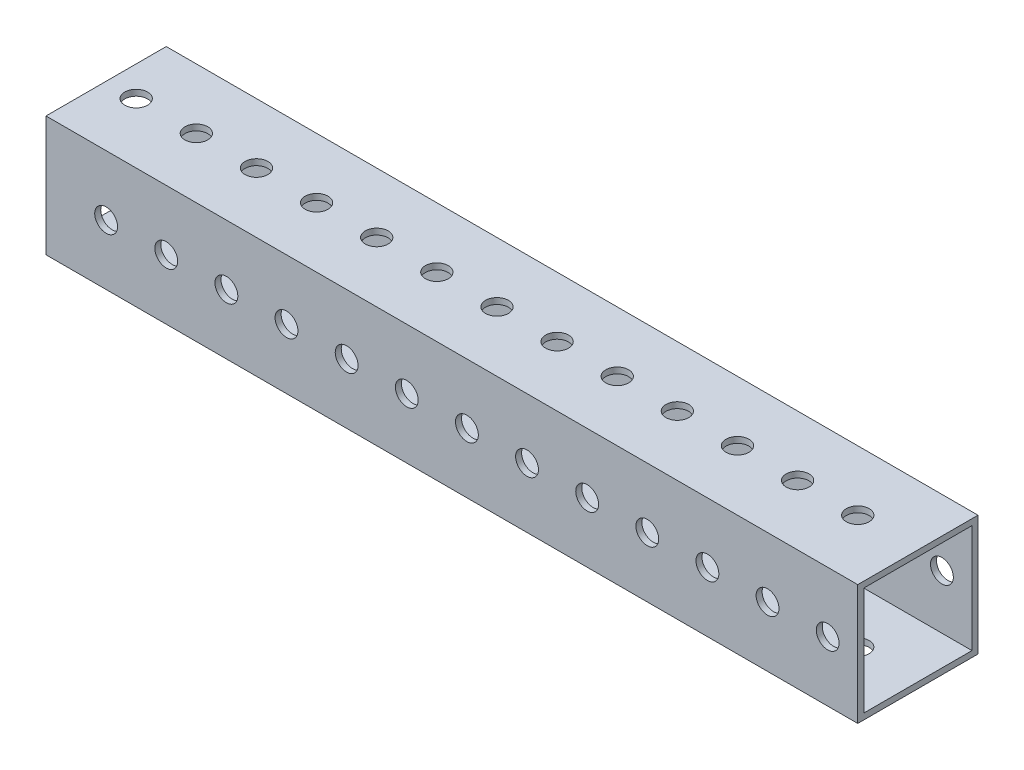
SolidWorks part; units mm, degrees
ref_plane "Front Plane" through (0, 0, 0) normal (0, 0, 1) x (1, 0, 0)
ref_plane "Top Plane" through (0, 0, 0) normal (0, 1, 0) x (1, 0, 0)
ref_plane "Right Plane" through (0, 0, 0) normal (1, 0, 0) x (0, 0, -1)
sketch "Sketch1" plane through (0, 0, 0) normal (0, 1, 0) x (1, 0, 0)
  line L1 (0, 0) -> (171.45, 0)
  line L2 (0, 0) -> (0, 25.4)
  line L3 (0, 25.4) -> (171.45, 25.4)
  line L4 (171.45, 0) -> (171.45, 25.4)
  dimension "D1" = 25.4
  dimension "D2" = 171.45
extrude "Boss-Extrude1" add sketch "Sketch1" along normal blind 25.4
sketch "Sketch2" plane through (171.45, 0, 0) normal (1, 0, 0) x (0, 0, -1)
  line L0 (0, 25.4) -> (25.4, 25.4) construction
  line L1 (25.4, 25.4) -> (25.4, 0) construction
  line L3 (1.27, 1.27) -> (24.13, 1.27)
  line L4 (1.27, 1.27) -> (1.27, 24.13)
  line L5 (1.27, 24.13) -> (24.13, 24.13)
  line L6 (24.13, 1.27) -> (24.13, 24.13)
  point P8 (12.7, 12.7)
  dimension "D1" = 22.86
  dimension "D2" = 1.27
  dimension "D3" = 1.27
extrude "Cut-Extrude1" cut sketch "Sketch2" against normal through all
sketch "Sketch3" plane through (0, 25.4, 0) normal (0, 1, 0) x (1, 0, 0)
  line L0 (171.45, 25.4) -> (0, 25.4) construction
  line L1 (0, 25.4) -> (0, 0) construction
  circle A0 centre (6.35, 12.7) radius 2.413
  circle A1 centre (19.05, 12.7) radius 2.413
  circle A2 centre (31.75, 12.7) radius 2.413
  circle A3 centre (44.45, 12.7) radius 2.413
  circle A4 centre (57.15, 12.7) radius 2.413
  circle A5 centre (69.85, 12.7) radius 2.413
  circle A6 centre (82.55, 12.7) radius 2.413
  circle A7 centre (95.25, 12.7) radius 2.413
  circle A8 centre (107.95, 12.7) radius 2.413
  circle A9 centre (120.65, 12.7) radius 2.413
  circle A10 centre (133.35, 12.7) radius 2.413
  circle A11 centre (146.05, 12.7) radius 2.413
  circle A12 centre (158.75, 12.7) radius 2.413
  dimension "D1" = 12.7
  dimension "D2" = 6.35
  dimension "D3" = 4.826
  dimension "D4" = 13
sketch "Sketch4" plane through (0, 0, -25.4) normal (0, 0, -1) x (-1, 0, 0)
  line L0 (-171.45, 25.4) -> (0, 25.4) construction
  line L1 (-171.45, 25.4) -> (-171.45, 0) construction
  circle A0 centre (-165.1, 12.7) radius 2.413
  circle A1 centre (-152.4, 12.7) radius 2.413
  circle A2 centre (-139.7, 12.7) radius 2.413
  circle A3 centre (-127, 12.7) radius 2.413
  circle A4 centre (-114.3, 12.7) radius 2.413
  circle A5 centre (-101.6, 12.7) radius 2.413
  circle A6 centre (-88.9, 12.7) radius 2.413
  circle A7 centre (-76.2, 12.7) radius 2.413
  circle A8 centre (-63.5, 12.7) radius 2.413
  circle A9 centre (-50.8, 12.7) radius 2.413
  circle A10 centre (-38.1, 12.7) radius 2.413
  circle A11 centre (-25.4, 12.7) radius 2.413
  circle A12 centre (-12.7, 12.7) radius 2.413
  dimension "D1" = 12.7
  dimension "D2" = 6.35
  dimension "D3" = 4.826
  dimension "D4" = 13
extrude "Cut-Extrude2" cut sketch "Sketch4" against normal through all
extrude "Cut-Extrude3" cut sketch "Sketch3" against normal through all
